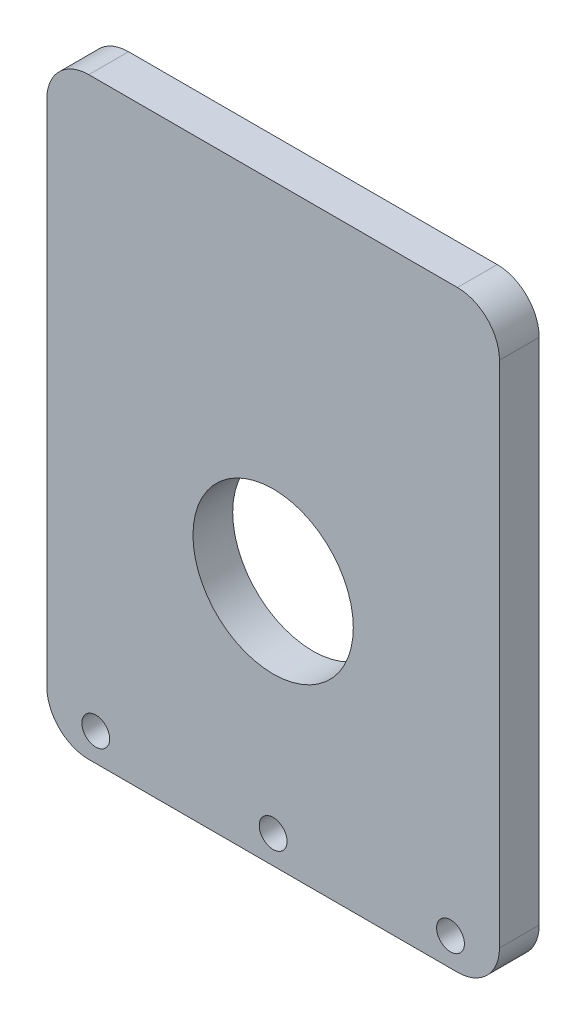
SolidWorks part; units mm, degrees
ref_plane "Front Plane" through (0, 0, 0) normal (0, 0, 1) x (1, 0, 0)
ref_plane "Top Plane" through (0, 0, 0) normal (0, 1, 0) x (1, 0, 0)
ref_plane "Right Plane" through (0, 0, 0) normal (1, 0, 0) x (0, 0, -1)
sketch "Sketch1" plane through (0, 0, 0) normal (0, 0, 1) x (1, 0, 0)
  line L0 (-4909.2583, 2119.4796) -> (-4843.2691, 2119.4796)
  line L1 (-4835.7507, 2111.9612) -> (-4835.7507, 2020.8387)
  line L2 (-4916.7767, 2111.9612) -> (-4916.7767, 2020.8387)
  line L3 (-4843.2691, 2013.3203) -> (-4909.2583, 2013.3203)
  arc A0 (-4835.7507, 2111.9612) -> (-4843.2691, 2119.4796) centre (-4843.2691, 2111.9612) ccw
  arc A1 (-4843.2691, 2013.3203) -> (-4835.7507, 2020.8387) centre (-4843.2691, 2020.8387) ccw
  arc A2 (-4909.2583, 2119.4796) -> (-4916.7767, 2111.9612) centre (-4909.2583, 2111.9612) ccw
  arc A3 (-4916.7767, 2020.8387) -> (-4909.2583, 2013.3203) centre (-4909.2583, 2020.8387) ccw
  circle A4 centre (-4876.2637, 2018.3495) radius 2.4892
  circle A5 centre (-4844.5137, 2018.3495) radius 2.4892
  circle A6 centre (-4908.0137, 2018.3495) radius 2.4892
  circle A7 centre (-4876.2637, 2057.4147) radius 14.351
extrude "Boss-Extrude1" add sketch "Sketch1" along normal blind 7.112
